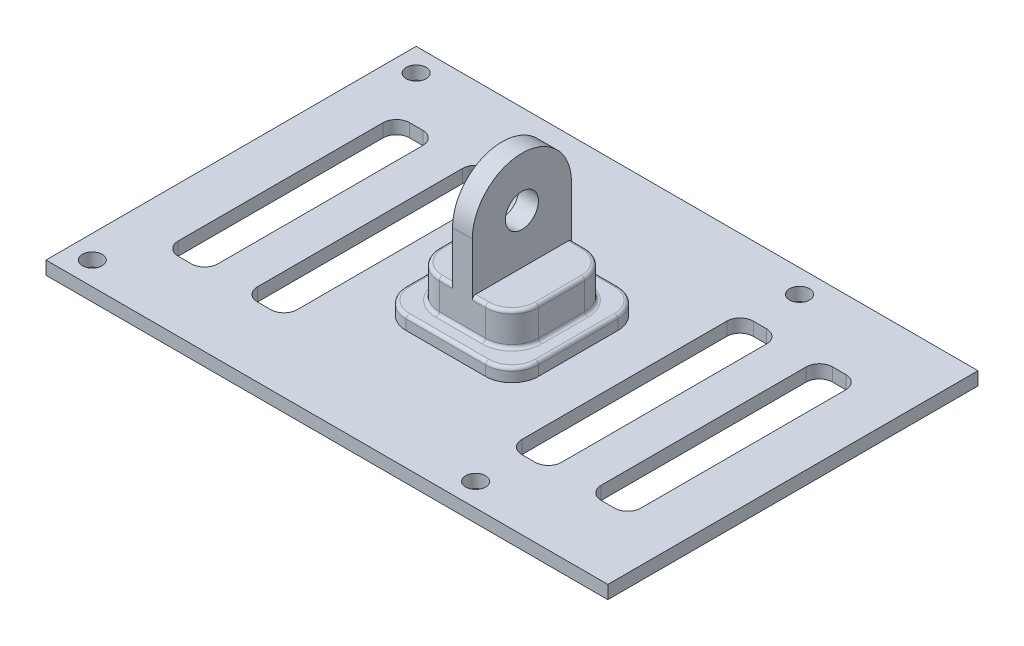
SolidWorks part; units mm, degrees
ref_plane "Front Plane" through (0, 0, 0) normal (0, 0, 1) x (1, 0, 0)
ref_plane "Top Plane" through (0, 0, 0) normal (0, 1, 0) x (1, 0, 0)
ref_plane "Right Plane" through (0, 0, 0) normal (1, 0, 0) x (0, 0, -1)
sketch "Sketch1" plane through (0, 0, 0) normal (0, 1, 0) x (1, 0, 0)
  line L1 (-42.5, -28) -> (42.5, -28)
  line L2 (-42.5, -28) -> (-42.5, 28)
  line L3 (-42.5, 28) -> (42.5, 28)
  line L4 (42.5, -28) -> (42.5, 28)
  line L5 (-42.5, -28) -> (42.5, 28) construction
  line L6 (-42.5, 28) -> (42.5, -28) construction
  point P0 (0, 0)
  dimension "D1" = 85
  dimension "D2" = 56
sketch "Sketch2" plane through (0, 0, 0) normal (0, 1, 0) x (1, 0, 0)
  line L0 (-42.5, -28) -> (-42.5, 28) construction
  line L1 (-42.5, -28) -> (42.5, -28) construction
  line L3 (-42.5, 28) -> (42.5, 28) construction
  circle A0 centre (-39, -24.5) radius 1.5
  circle A1 centre (-39, 24.5) radius 1.5
  circle A2 centre (19, 24.5) radius 1.5
  circle A3 centre (19, -24.5) radius 1.5
  point P12 (0, 0)
  point P14 (-37.5, 10.9451)
  point P15 (0, 0)
  point P16 (0, 0)
  dimension "D1" = 3
  dimension "D4" = 3
  dimension "D7" = 3
  dimension "D9" = 3
  dimension "D2" = 3.5
  dimension "D3" = 3.5
  dimension "D5" = 3.5
  dimension "D6" = 3.5
  dimension "D8" = 58
  dimension "D10" = 58
extrude "Boss-Extrude1" add sketch "Sketch1" along normal blind 2
extrude "Cut-Extrude2" cut sketch "Sketch2" along normal blind 2
sketch "Sketch3" plane through (0, 2, 0) normal (0, 1, 0) x (1, 0, 0)
  line L1 (-10, -10) -> (10, -10)
  line L2 (-10, -10) -> (-10, 10)
  line L3 (-10, 10) -> (10, 10)
  line L4 (10, -10) -> (10, 10)
  line L5 (-10, -10) -> (10, 10) construction
  line L6 (-10, 10) -> (10, -10) construction
  point P0 (0, 0)
  dimension "D1" = 20
  dimension "D2" = 20
extrude "Boss-Extrude2" add sketch "Sketch3" along normal blind 2
sketch "Sketch4" plane through (0, 4, 0) normal (0, 1, 0) x (1, 0, 0)
  line L1 (-7.5, -7.5) -> (7.5, -7.5)
  line L2 (-7.5, -7.5) -> (-7.5, 7.5)
  line L3 (-7.5, 7.5) -> (7.5, 7.5)
  line L4 (7.5, -7.5) -> (7.5, 7.5)
  line L5 (-7.5, -7.5) -> (7.5, 7.5) construction
  line L6 (-7.5, 7.5) -> (7.5, -7.5) construction
  point P0 (0, 0)
  dimension "D1" = 15
  dimension "D2" = 15
extrude "Boss-Extrude3" add sketch "Sketch4" along normal blind 5
sketch "Sketch5" plane through (0, 9, 0) normal (0, 1, 0) x (1, 0, 0)
  line L0 (7.5, 7.5) -> (-7.5, 7.5) construction
  line L1 (-1.5, -7.5) -> (1.5, -7.5)
  line L2 (-1.5, -7.5) -> (-1.5, 7.5)
  line L3 (-1.5, 7.5) -> (1.5, 7.5)
  line L4 (1.5, -7.5) -> (1.5, 7.5)
  line L5 (-1.5, -7.5) -> (1.5, 7.5) construction
  line L6 (-1.5, 7.5) -> (1.5, -7.5) construction
  point P0 (0, 0)
  dimension "D1" = 3
extrude "Boss-Extrude4" add sketch "Sketch5" along normal blind 15
sketch "Sketch6" plane through (-1.5, 0, 0) normal (-1, 0, 0) x (0, 0, 1)
  line L0 (-7.5, 9) -> (7.5, 9) construction
  line L1 (-7.5, 24) -> (7.5, 24) construction
  line L2 (-7.5, 16.5) -> (-7.5, 9)
  line L3 (-7.5, 9) -> (7.5, 9)
  line L4 (7.5, 9) -> (7.5, 16.5)
  arc A0 (7.5, 16.5) -> (-7.5, 16.5) centre (0, 16.5) ccw
  point P5 (0, 9)
  dimension "D1" = 15
sketch "Sketch7" plane through (-1.5, 0, 0) normal (-1, 0, 0) x (0, 0, 1)
  line L0 (-7.5, 16.5) -> (-7.5, 24)
  line L1 (-7.5, 24) -> (0, 24)
  arc A0 (7.5, 16.5) -> (-7.5, 16.5) centre (0, 16.5) ccw construction
  arc A3 (0, 24) -> (-7.5, 16.5) centre (0, 16.5) ccw
extrude "Cut-Extrude3" cut sketch "Sketch7" against normal blind 15
sketch "Sketch8" plane through (-1.5, 0, 0) normal (-1, 0, 0) x (0, 0, 1)
  line L0 (7.5, 16.5) -> (7.5, 24)
  line L2 (7.5, 24) -> (0, 24)
  arc A0 (7.5, 16.5) -> (-7.5, 16.5) centre (0, 16.5) ccw construction
  arc A1 (7.5, 16.5) -> (0, 24) centre (0, 16.5) ccw
extrude "Cut-Extrude4" cut sketch "Sketch8" against normal blind 15
sketch "Sketch9" plane through (-1.5, 0, 0) normal (-1, 0, 0) x (0, 0, 1)
  circle A0 centre (0, 16.5) radius 2.5
  dimension "D1" = 5
extrude "Cut-Extrude5" cut sketch "Sketch9" against normal blind 15
fillet "Fillet1" radius 4 8 edges at (7.5, 6.5, 7.5) (-7.5, 6.5, 7.5) (-7.5, 6.5, -7.5) (7.5, 6.5, -7.5) (10, 3, 10) (-10, 3, 10) (-10, 3, -10) (10, 3, -10)
fillet "Fillet2" radius 0.5 16 edges at (6.3284, 4, -6.3284) (0, 4, -7.5) (-6.3284, 4, -6.3284) (-7.5, 4, 0) (-6.3284, 4, 6.3284) (0, 4, 7.5) (6.3284, 4, 6.3284) (7.5, 4, 0) (-8.8284, 4, 8.8284) (-10, 4, 0) (-8.8284, 4, -8.8284) (0, 4, -10) (8.8284, 4, -8.8284) (10, 4, 0) (8.8284, 4, 8.8284) (0, 4, 10)
fillet "Fillet3" radius 0.5 10 edges at (-2.5, 9, -7.5) (-6.3284, 9, -6.3284) (-2.5, 9, 7.5) (-6.3284, 9, 6.3284) (2.5, 9, 7.5) (2.5, 9, -7.5) (6.3284, 9, -6.3284) (7.5, 9, 0) (-7.5, 9, 0) (6.3284, 9, 6.3284)
sketch "Sketch10" plane through (0, 2, 0) normal (0, 1, 0) x (1, 0, 0)
  line L1 (-21, -17.5) -> (-19, -17.5)
  line L2 (-23, -15.5) -> (-23, 15.5)
  line L3 (-21, 17.5) -> (-19, 17.5)
  line L4 (-17, -15.5) -> (-17, 15.5)
  line L5 (-23, -17.5) -> (-17, 17.5) construction
  line L6 (-23, 17.5) -> (-17, -17.5) construction
  line L10 (0, 46.514) -> (0, -32.6914) construction
  line L19 (-35, -15.5) -> (-35, 15.5)
  line L20 (-33, -17.5) -> (-31, -17.5)
  line L21 (-29, -15.5) -> (-29, 15.5)
  line L22 (-33, 17.5) -> (-31, 17.5)
  line L23 (33, -17.5) -> (31, -17.5)
  line L24 (29, -15.5) -> (29, 15.5)
  line L25 (33, 17.5) -> (31, 17.5)
  line L26 (35, -15.5) -> (35, 15.5)
  line L27 (21, 17.5) -> (19, 17.5)
  line L28 (17, -15.5) -> (17, 15.5)
  line L29 (21, -17.5) -> (19, -17.5)
  line L30 (23, -15.5) -> (23, 15.5)
  arc A0 (-19, -17.5) -> (-17, -15.5) centre (-19, -15.5) ccw
  arc A1 (-21, -17.5) -> (-23, -15.5) centre (-21, -15.5) cw
  arc A2 (-19, 17.5) -> (-17, 15.5) centre (-19, 15.5) cw
  arc A3 (-23, 15.5) -> (-21, 17.5) centre (-21, 15.5) cw
  arc A4 (-35, 15.5) -> (-33, 17.5) centre (-33, 15.5) cw
  arc A5 (-33, -17.5) -> (-35, -15.5) centre (-33, -15.5) cw
  arc A6 (-31, -17.5) -> (-29, -15.5) centre (-31, -15.5) ccw
  arc A7 (-31, 17.5) -> (-29, 15.5) centre (-31, 15.5) cw
  arc A8 (33, -17.5) -> (35, -15.5) centre (33, -15.5) ccw
  arc A9 (31, -17.5) -> (29, -15.5) centre (31, -15.5) cw
  arc A10 (31, 17.5) -> (29, 15.5) centre (31, 15.5) ccw
  arc A11 (35, 15.5) -> (33, 17.5) centre (33, 15.5) ccw
  arc A12 (19, 17.5) -> (17, 15.5) centre (19, 15.5) ccw
  arc A13 (19, -17.5) -> (17, -15.5) centre (19, -15.5) cw
  arc A14 (21, -17.5) -> (23, -15.5) centre (21, -15.5) ccw
  arc A15 (23, 15.5) -> (21, 17.5) centre (21, 15.5) ccw
  point P0 (-20, 0)
  dimension "D5" = 2
  dimension "D1" = 20
  dimension "D2" = 6
  dimension "D3" = 35
  dimension "D4" = 2
extrude "Cut-Extrude6" cut sketch "Sketch10" against normal blind 15
